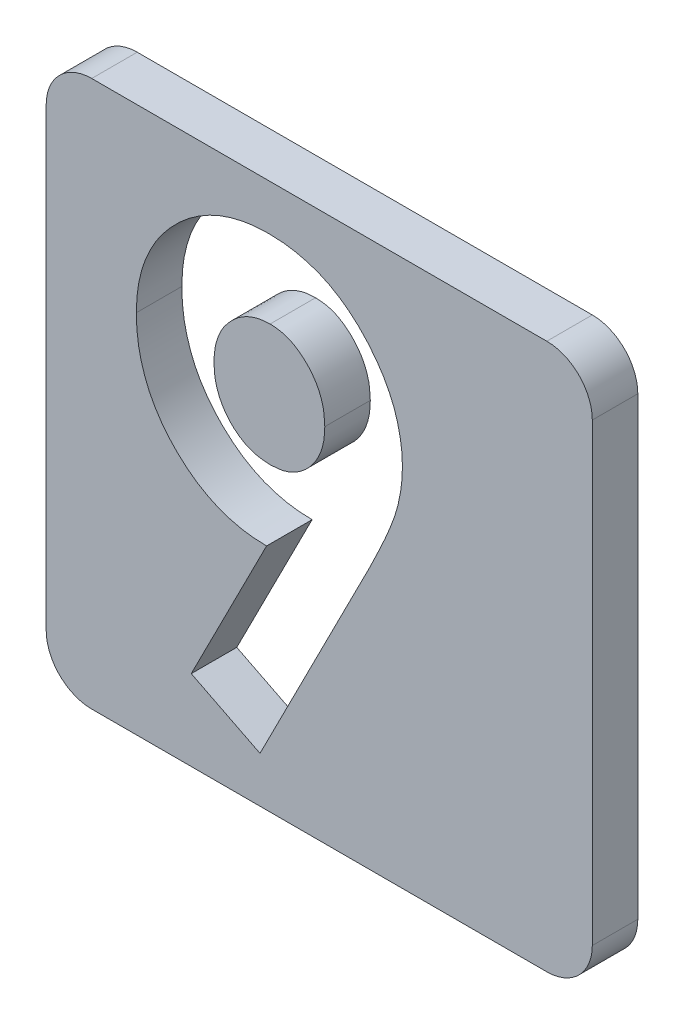
SolidWorks part; units mm, degrees
ref_plane "Front Plane" through (0, 0, 0) normal (0, 0, 1) x (1, 0, 0)
ref_plane "Top Plane" through (0, 0, 0) normal (0, 1, 0) x (1, 0, 0)
ref_plane "Right Plane" through (0, 0, 0) normal (1, 0, 0) x (0, 0, -1)
sketch "Sketch1" plane through (0, 0, 0) normal (0, 0, 1) x (1, 0, 0)
  line L1 (-50, 60) -> (50, 60)
  line L2 (-60, 50) -> (-60, -50)
  line L3 (-50, -60) -> (50, -60)
  line L4 (60, 50) -> (60, -50)
  line L5 (-60, 60) -> (60, -60) construction
  line L6 (-60, -60) -> (60, 60) construction
  arc A0 (-60, -50) -> (-50, -60) centre (-50, -50) ccw
  arc A1 (50, -60) -> (60, -50) centre (50, -50) ccw
  arc A2 (50, 60) -> (60, 50) centre (50, 50) cw
  arc A3 (-50, 60) -> (-60, 50) centre (-50, 50) ccw
  point P0 (0, 0)
  dimension "D3" = 10
  dimension "D1" = 120
  dimension "D2" = 120
extrude "Boss-Extrude1" add sketch "Sketch1" along normal blind 10 contours A3 L2 A0 L3 A1 L4 A2 L1
sketch "Sketch2" plane through (0, 0, 10) normal (0, 0, 1) x (1, 0, 0)
  line L0 (0, 0) -> (0, 40) construction
  line L1 (-50, 50) -> (50, 50) construction
  line L2 (-50, 50) -> (-50, -50) construction
  line L3 (-50, -50) -> (50, -50) construction
  line L4 (50, 50) -> (50, -50) construction
  line L5 (-50, 50) -> (50, -50) construction
  line L6 (-50, -50) -> (50, 50) construction
  line L7 (0, 40) -> (-40, 40) construction
  line L8 (-40, 40) -> (-40, 0) construction
  line L9 (-40, 0) -> (0, 0) construction
  line L11 (0, 20) -> (-20, 20) construction
  line L12 (-20, 40) -> (-20, 20) construction
  circle A0 centre (0, 40) radius 4 construction
  circle A1 centre (0, 20) radius 4 construction
  circle A2 centre (0, 0) radius 4 construction
  circle A3 centre (-20, 20) radius 4 construction
  circle A4 centre (-20, 40) radius 4 construction
  circle A5 centre (-40, 40) radius 4 construction
  circle A6 centre (0, 0) radius 4 construction
  circle A7 centre (20, 0) radius 4 construction
  circle A8 centre (40, 0) radius 4 construction
  circle A9 centre (40, 20) radius 4 construction
  circle A10 centre (40, 40) radius 4 construction
  circle A11 centre (20, 20) radius 4 construction
  circle A12 centre (0, 0) radius 4 construction
  circle A13 centre (0, -20) radius 4 construction
  circle A14 centre (0, -40) radius 4 construction
  circle A15 centre (20, -40) radius 4 construction
  circle A16 centre (40, -40) radius 4 construction
  circle A17 centre (20, -20) radius 4 construction
  circle A18 centre (0, 0) radius 4 construction
  circle A19 centre (-20, 0) radius 4 construction
  circle A20 centre (-40, 0) radius 4 construction
  circle A21 centre (-40, -20) radius 4 construction
  circle A22 centre (-40, -40) radius 4 construction
  circle A23 centre (-20, -20) radius 4 construction
  text T0 "9" font "Century Gothic" height 95
  point P0 (0, 0)
  point P55 (0, 0)
  dimension "D4" = 8
  dimension "D1" = 100
  dimension "D2" = 100
  dimension "D3" = 40
  dimension "D5" = 4
extrude "Cut-Extrude8" cut sketch "Sketch2" against normal blind 10
